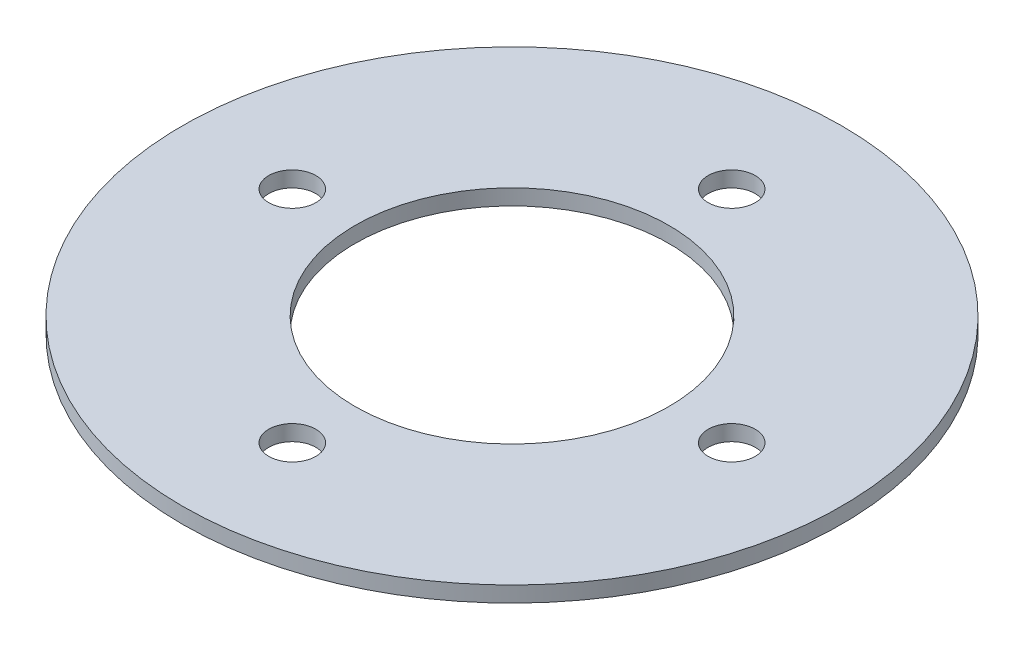
SolidWorks part; units mm, degrees
ref_plane "前视基准面" through (0, 0, 0) normal (0, 0, 1) x (1, 0, 0)
ref_plane "上视基准面" through (0, 0, 0) normal (0, 1, 0) x (1, 0, 0)
ref_plane "右视基准面" through (0, 0, 0) normal (1, 0, 0) x (0, 0, -1)
other "Configuration Table"
sketch "草图1" plane through (0, 0, 0) normal (0, 1, 0) x (1, 0, 0)
  circle A0 centre (0, 0) radius 21
  circle A1 centre (0, 0) radius 10
  circle A2 centre (14, 0) radius 1.5
  circle A3 centre (0, -14) radius 1.5
  circle A4 centre (-14, 0) radius 1.5
  circle A5 centre (0, 14) radius 1.5
  dimension "D1" = 42
  dimension "D2" = 20
  dimension "D3" = 3
  dimension "D4" = 14
extrude "凸台-拉伸2" add sketch "草图1" along normal blind 1 contours A0 A5 A4 A3 A2 A1
